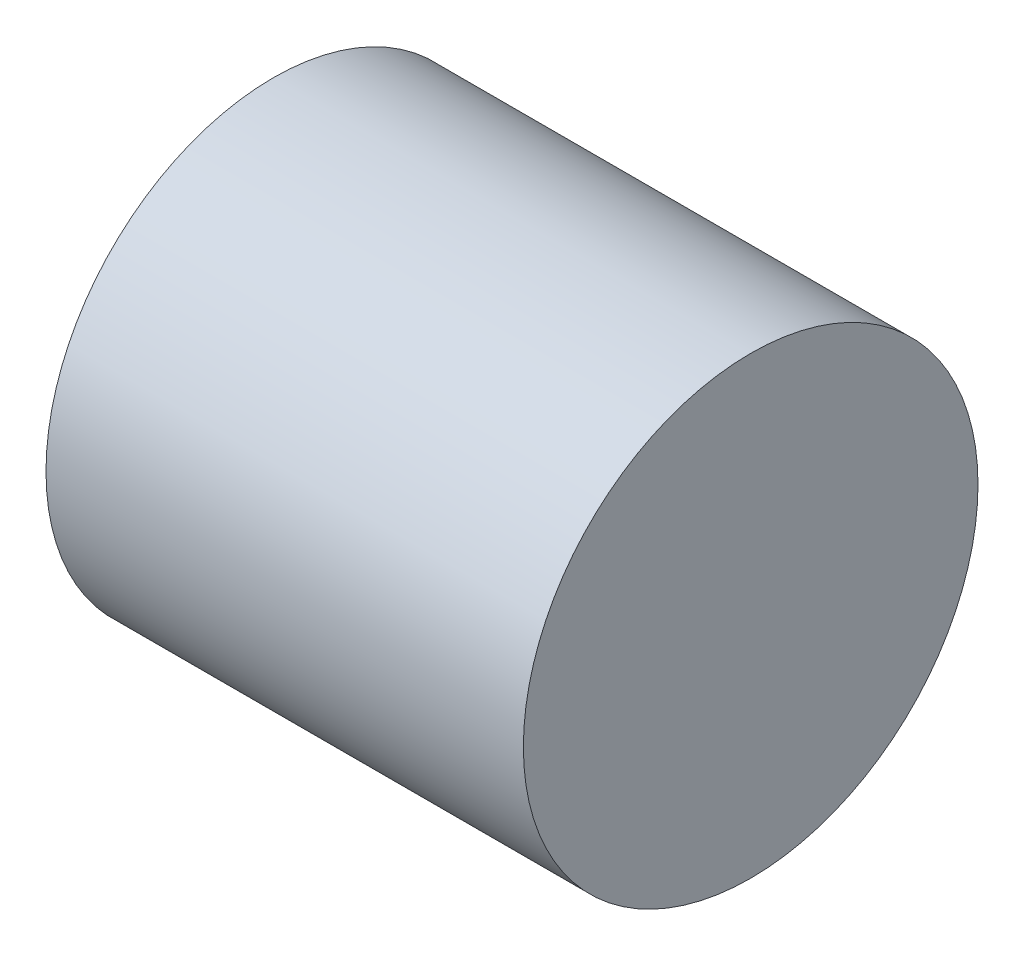
SolidWorks part; units mm, degrees
ref_plane "Front Plane" through (0, 0, 0) normal (0, 0, 1) x (1, 0, 0)
ref_plane "Top Plane" through (0, 0, 0) normal (0, 1, 0) x (1, 0, 0)
ref_plane "Right Plane" through (0, 0, 0) normal (1, 0, 0) x (0, 0, -1)
sketch "Sketch1" plane through (0, 0, 0) normal (1, 0, 0) x (0, 0, -1)
  circle A0 centre (0, 0) radius 8
  dimension "D1" = 16
extrude "Boss-Extrude1" add sketch "Sketch1" along normal blind 16.8
